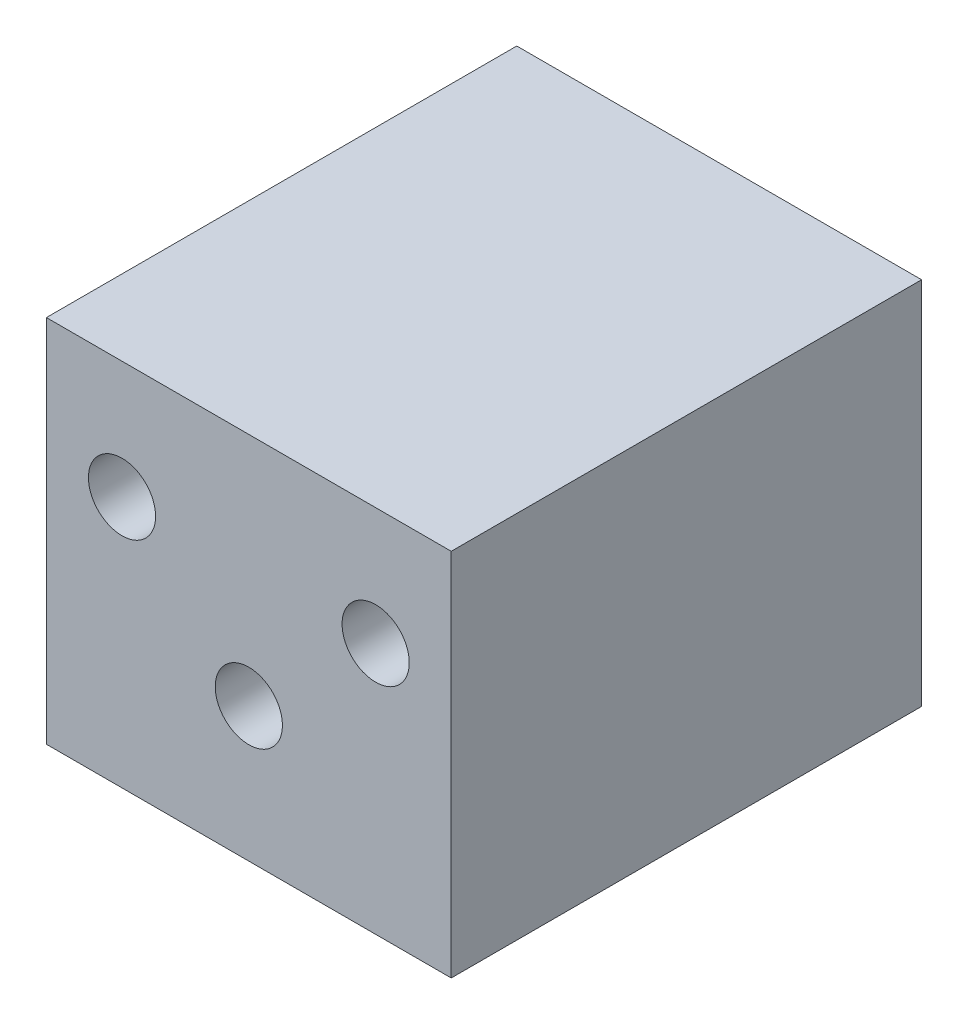
SolidWorks part; units mm, degrees
ref_plane "Alzado" through (0, 0, 0) normal (0, 0, 1) x (1, 0, 0)
ref_plane "Planta" through (0, 0, 0) normal (0, 1, 0) x (1, 0, 0)
ref_plane "Vista lateral" through (0, 0, 0) normal (1, 0, 0) x (0, 0, -1)
sketch "Croquis1" plane through (0, 0, 0) normal (0, 0, 1) x (1, 0, 0)
  line L0 (-12.05, 4) -> (-7.55, 4) construction
  line L1 (-12.05, 11) -> (12.05, 11)
  line L2 (-12.05, 11) -> (-12.05, -11)
  line L3 (-12.05, -11) -> (12.05, -11)
  line L4 (12.05, 11) -> (12.05, -11)
  line L5 (-12.05, 11) -> (12.05, -11) construction
  line L6 (-12.05, -11) -> (12.05, 11) construction
  line L7 (-7.55, 4) -> (7.55, 4) construction
  line L8 (7.55, 4) -> (12.05, 4) construction
  circle A0 centre (-7.55, 4) radius 2
  circle A1 centre (7.55, 4) radius 2
  point P0 (0, 0)
  dimension "D3" = 4
  dimension "D4" = 4
  dimension "D1" = 22
  dimension "D2" = 24.1
  dimension "D5" = 4.5
  dimension "D6" = 4.5
  dimension "D7" = 7
extrude "Saliente-Extruir1" add sketch "Croquis1" along normal blind 28
sketch "Croquis2" plane through (0, 0, 28) normal (0, 0, 1) x (1, 0, 0)
  line L0 (-12.05, -11) -> (12.05, -11) construction
  line L1 (0, -3) -> (0, 0) construction
  circle A0 centre (0, -3) radius 2
  dimension "D1" = 8
extrude "Cortar-Extruir1" cut sketch "Croquis2" against normal blind 3
